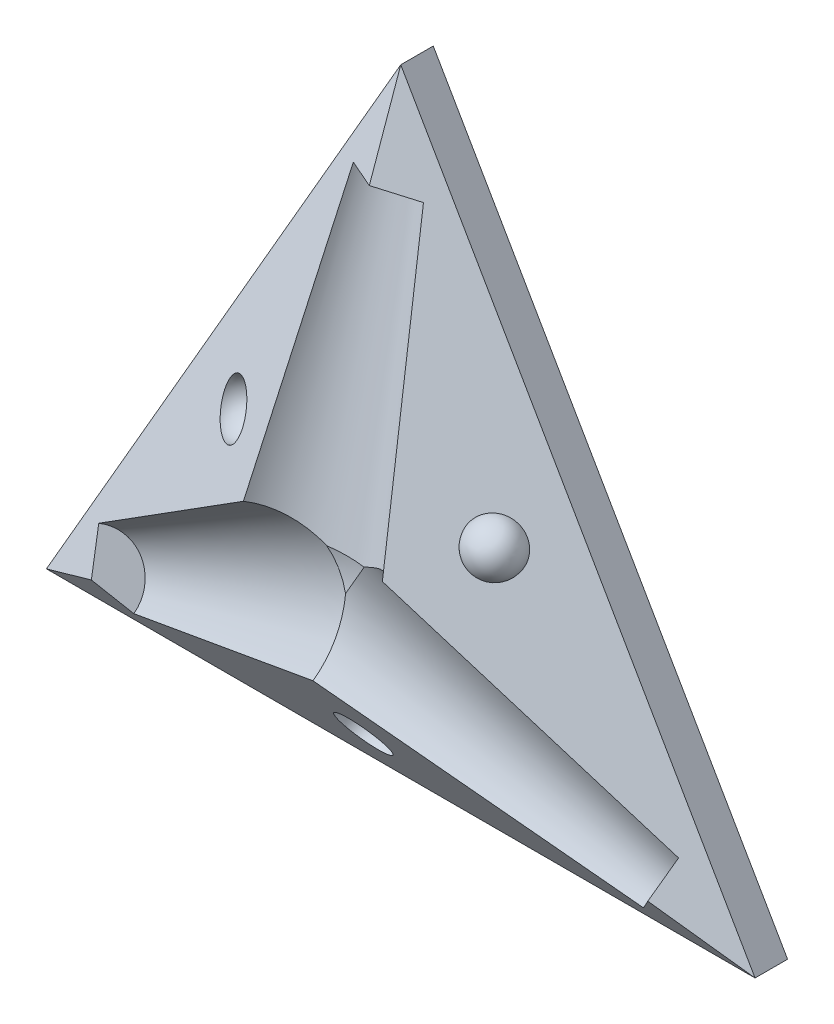
SolidWorks part; units mm, degrees
ref_plane "Top Plane" through (0, 0, 0) normal (0, 0, 1) x (1, 0, 0)
ref_plane "Front Plane" through (0, 0, 0) normal (0, 1, 0) x (1, 0, 0)
ref_plane "Right Plane" through (0, 0, 0) normal (1, 0, 0) x (0, 0, -1)
sketch "Sketch1" plane through (0, 0, 0) normal (0, 0, 1) x (1, 0, 0)
  line L1 (0, 80.829) -> (-70, -40.4145)
  line L2 (-70, -40.4145) -> (70, -40.4145)
  line L3 (70, -40.4145) -> (0, 80.829)
  circle A0 centre (0, 0) radius 40.4145 construction
  dimension "D1" = 140
extrude "Boss-Extrude1" add sketch "Sketch1" along normal blind 35
sketch3d "3DSketch1"
  line L0 (-35, 20.2073, 35) -> (70, -40.4145, 35) construction
  line L1 (0, 80.829, 35) -> (-70, -40.4145, 35) construction
  line L2 (-70, -40.4145, 35) -> (35, 20.2073, 35) construction
  line L3 (70, -40.4145, 35) -> (0, 80.829, 35) construction
  line L4 (0, 80.829, 35) -> (0, -40.4145, 35) construction
  line L5 (-70, -40.4145, 35) -> (70, -40.4145, 35) construction
  line L6 (0, 0, 35) -> (0, -40.4145, 6.4226) construction
  line L7 (0, 0, 35) -> (35, 20.2073, 6.4226) construction
  line L8 (35, 20.2073, 35) -> (35, 20.2073, 0) construction
  line L9 (70, -40.4145, 0) -> (0, 80.829, 0) construction
  line L10 (-35, 20.2073, 35) -> (-35, 20.2073, 0) construction
  line L11 (0, 80.829, 0) -> (-70, -40.4145, 0) construction
  line L12 (0, 0, 35) -> (-35, 20.2073, 6.4226) construction
  line L13 (0, -40.4145, 35) -> (0, -40.4145, 0) construction
  line L14 (-70, -40.4145, 0) -> (70, -40.4145, 0) construction
  line L15 (35, 20.2073, 6.4226) -> (70, -40.4145, 6.4226) construction
  line L16 (70, -40.4145, 35) -> (70, -40.4145, 0) construction
  line L17 (70, -40.4145, 6.4226) -> (0, -40.4145, 6.4226) construction
  line L18 (0, -40.4145, 6.4226) -> (-70, -40.4145, 6.4226) construction
  line L19 (-70, -40.4145, 35) -> (-70, -40.4145, 0) construction
  line L20 (-70, -40.4145, 6.4226) -> (-35, 20.2073, 6.4226) construction
  line L21 (-35, 20.2073, 6.4226) -> (0, 80.829, 6.4226) construction
  line L22 (0, 80.829, 35) -> (0, 80.829, 0) construction
  line L23 (0, 80.829, 6.4226) -> (35, 20.2073, 6.4226) construction
  point P15 (0, 0, 35)
  dimension "D1" = 35.264
  dimension "D2" = 35.264
  dimension "D3" = 35.264
ref_plane "Plane3" through (-14.2887, 8.2496, 23.3333) normal (-0.5, 0.2887, 0.8165) x (0.8656, 0.1356, 0.4821)
ref_plane "Plane4" through (14.2887, 8.2496, 23.3333) normal (-0.5, -0.2887, -0.8165) x (-0.8657, 0.1407, 0.4804)
ref_plane "Plane5" through (0, -16.4992, 23.3333) normal (0, 0.5774, -0.8165) x (-1, -0.0044, -0.0031)
sketch "Sketch17" plane through (-14.2887, 8.2496, 23.3333) normal (-0.5, 0.2887, 0.8165) x (0.8656, 0.1356, 0.4821)
  line L1 (50.7051, 91.4418) -> (-82.3069, 91.4418)
  line L2 (50.7051, 91.4418) -> (50.7051, -58.5784)
  line L3 (50.7051, -58.5784) -> (-82.3069, -58.5784)
  line L4 (-82.3069, 91.4418) -> (-82.3069, -58.5784)
extrude "Cut-Extrude1" cut sketch "Sketch17" along normal blind 100
sketch "Sketch18" plane through (0, -16.4992, 23.3333) normal (0, 0.5774, -0.8165) x (-1, -0.0044, -0.0031)
  line L1 (-108.8296, 85.8645) -> (83.5835, 85.8645)
  line L2 (-108.8296, 85.8645) -> (-108.8296, -66.0789)
  line L3 (-108.8296, -66.0789) -> (83.5835, -66.0789)
  line L4 (83.5835, 85.8645) -> (83.5835, -66.0789)
extrude "Cut-Extrude2" cut sketch "Sketch18" against normal blind 100
sketch "Sketch19" plane through (14.2887, 8.2496, 23.3333) normal (-0.5, -0.2887, -0.8165) x (-0.8657, 0.1407, 0.4804)
  line L1 (-107.5238, 116.8457) -> (105.5056, 116.8457)
  line L2 (-107.5238, 116.8457) -> (-107.5238, -68.1619)
  line L3 (-107.5238, -68.1619) -> (105.5056, -68.1619)
  line L4 (105.5056, 116.8457) -> (105.5056, -68.1619)
extrude "Cut-Extrude3" cut sketch "Sketch19" against normal blind 100
ref_plane "Plane6" through (0, 0, 35) normal (0, 0, -1) x (-1, 0, 0)
sketch "Sketch2" plane through (0, 0, 35) normal (0, 0, 1) x (1, 0, 0)
  line L0 (0, 0) -> (18.1463, 0) construction
  line L1 (18.1463, 0) -> (-18.1463, 0)
  arc A0 (18.1463, 0) -> (-18.1463, 0) centre (0, 0) ccw
revolve "Cut-Revolve3" cut sketch "Sketch2" angle 360 about L0
sketch "Sketch3" plane through (14.2887, 8.2496, 23.3333) normal (0.5, 0.2887, 0.8165) x (0.8657, -0.1407, -0.4804)
  line L0 (45.9966, -35.3768) -> (48.8695, -27.9104)
  line L2 (48.8695, -27.9104) -> (-3.5997, 1.2283)
  line L3 (45.9966, -35.3768) -> (0.1224, -17.7255)
  line L4 (63.1999, -41.9962) -> (0.1224, -17.7255) construction
  arc A1 (0.1224, -17.7255) -> (-16.3149, 6.9305) centre (-16.8135, -11.209) ccw construction
  arc A3 (0.1224, -17.7255) -> (-3.5997, 1.2283) centre (-16.8135, -11.209) ccw
  dimension "D1" = 8
  dimension "D2" = 8
sketch "Sketch10" plane through (0, -16.4992, 23.3333) normal (0, -0.5774, 0.8165) x (1, 0.0044, 0.0031)
  line L0 (-55.0957, -18.3845) -> (-50.5121, -24.9412)
  line L2 (-50.5121, -24.9412) -> (3.0568, 2.3018)
  line L3 (-14.7638, 9.8101) -> (-55.0957, -18.3845)
  line L4 (-70.1566, -28.9131) -> (-14.7638, 9.8101) construction
  arc A1 (-14.7638, 9.8101) -> (14.8685, 9.6506) centre (0.1088, 20.207) ccw construction
  arc A2 (-14.7638, 9.8101) -> (14.8685, 9.6506) centre (0.1088, 20.207) ccw
  dimension "D1" = 8
  dimension "D2" = 8
sketch "Sketch11" plane through (-14.2887, 8.2496, 23.3333) normal (-0.5, 0.2887, 0.8165) x (0.8656, 0.1356, 0.4821)
  line L0 (16.2774, 7.0182) -> (14.669, 55.9497)
  line L2 (14.669, 55.9497) -> (6.6733, 55.6869)
  line L3 (6.6733, 55.6869) -> (0.3071, -3.7128)
  line L4 (16.2774, 7.0182) -> (14.057, 74.5675) construction
  arc A1 (16.2774, 7.0182) -> (-0.027, -17.7259) centre (16.8735, -11.1183) ccw construction
  arc A4 (16.2774, 7.0182) -> (-0.027, -17.7259) centre (16.8735, -11.1183) ccw
  dimension "D1" = 8
  dimension "D3" = 8
revolve "Cut-Revolve7" cut sketch "Sketch11" angle 360 about L0
revolve "Cut-Revolve8" cut sketch "Sketch3" angle 360 about L3
revolve "Cut-Revolve9" cut sketch "Sketch10" angle 360 about L3
sketch "Sketch13" plane through (14.2887, 8.2496, 23.3333) normal (0.5, 0.2887, 0.8165) x (0.8657, -0.1407, -0.4804)
  line L0 (24.3709, 16.2473) -> (3.0899, 2.0599) construction
  line L2 (9.5701, 6.3801) -> (17.8907, 11.9271)
  line L3 (-14.4581, 74.4908) -> (63.1999, -41.9962) construction
  arc A1 (9.5701, 6.3801) -> (17.8907, 11.9271) centre (13.7304, 9.1536) ccw
  dimension "D1" = 10
revolve "Revolve2" add sketch "Sketch13" angle 360 about L0
sketch "Sketch14" plane through (-14.2887, 8.2496, 23.3333) normal (-0.5, 0.2887, 0.8165) x (0.8656, 0.1356, 0.4821)
  line L0 (-24.458, 16.1159) -> (0.6631, -0.3911) construction
  line L2 (-7.6353, 5.0617) -> (-16.1596, 10.663)
  line L3 (-62.973, -42.3358) -> (14.057, 74.5675) construction
  arc A1 (-16.1596, 10.663) -> (-7.6353, 5.0617) centre (-11.8975, 7.8624) ccw
  dimension "D1" = 10.2
revolve "Cut-Revolve10" cut sketch "Sketch14" angle 360 about L0
sketch "Sketch16" plane through (0, -16.4992, 23.3333) normal (0, -0.5774, 0.8165) x (1, 0, 0)
  line L0 (0, -29.2902) -> (0, -3.7136) construction
  line L2 (0, -21.6019) -> (0, -11.4019)
  line L3 (70, -29.2902) -> (-70, -29.2902) construction
  arc A1 (0, -21.6019) -> (0, -11.4019) centre (0, -16.5019) ccw
  dimension "D1" = 10.2
revolve "Cut-Revolve11" cut sketch "Sketch16" angle 360 about L0
equation "\"Leg Taper Angle\"= 8deg"
equation "\"Leg Length\"= 45mm"
equation "\"End Radius\"= 8mm"
equation "\"D1@Sketch3\"=\"Leg Taper Angle\""
equation "\"D2@Sketch3\"=\"End Radius\""
equation "\"D1@Sketch10\"=\"End Radius\""
equation "\"D2@Sketch10\"=\"Leg Taper Angle\""
equation "\"D1@Sketch11\"=\"Leg Taper Angle\""
equation "\"D3@Sketch11\"=\"End Radius\""
equation "\"Tetrahedron Angle\"= arccos ( 1 / 3 ) / 2"
equation "\"D3@3DSketch1\"=\"Tetrahedron Angle\""
equation "\"D2@3DSketch1\"=\"Tetrahedron Angle\""
equation "\"D1@3DSketch1\"=\"Tetrahedron Angle\""
